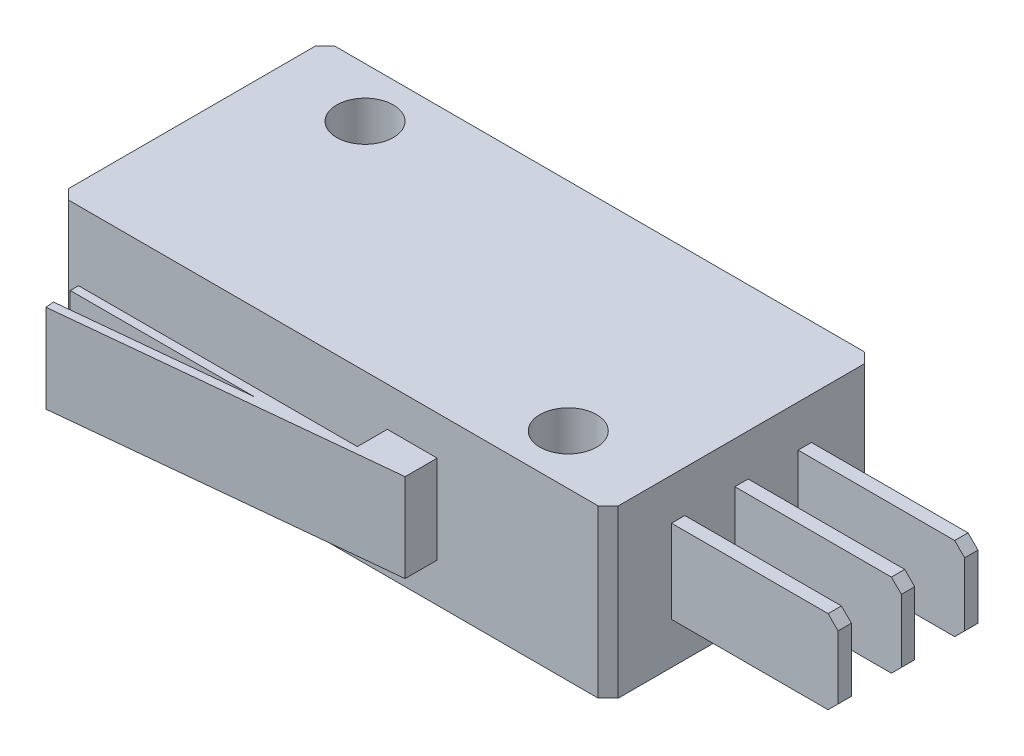
SolidWorks part; units mm, degrees
ref_plane "前视基准面" through (0, 0, 0) normal (0, 0, 1) x (1, 0, 0)
ref_plane "上视基准面" through (0, 0, 0) normal (0, 1, 0) x (1, 0, 0)
ref_plane "右视基准面" through (0, 0, 0) normal (1, 0, 0) x (0, 0, -1)
sketch "草图1" plane through (0, 0, 0) normal (0, 1, 0) x (1, 0, 0)
  line L0 (16.5, 0) -> (-16.5, 0) construction
  line L1 (-16.5, 8) -> (16.5, 8)
  line L2 (-16.5, 8) -> (-16.5, -8)
  line L3 (-16.5, -8) -> (16.5, -8)
  line L4 (16.5, 8) -> (16.5, -8)
  circle A0 centre (-11.1, 5) radius 1.7
  circle A1 centre (11.1, -5) radius 1.7
  point P4 (0, 8)
  point P6 (16.5, 0)
  dimension "D3" = 3.4
  dimension "D1" = 16
  dimension "D2" = 33
  dimension "D4" = 10
  dimension "D5" = 5
  dimension "D6" = 22.2
  dimension "D7" = 11.1
extrude "凸台-拉伸1" add sketch "草图1" along normal mid plane 10
sketch "草图2" plane through (0, 0, 0) normal (0, 1, 0) x (1, 0, 0)
  line L0 (3.237, -9.8) -> (-13.4989, -9.8)
  line L1 (-13.4989, -9.8) -> (-13.4989, -10.3)
  line L2 (-13.4989, -10.3) -> (-2.4578, -10.3)
  line L3 (6.2318, -9.9273) -> (6.2318, -4.6069)
  line L4 (3.237, -9.8) -> (3.237, -4.7223)
  line L5 (-13.3542, -11.9) -> (6.2318, -9.9273)
  line L7 (-13.4043, -11.4025) -> (-2.4578, -10.3)
  line L8 (-13.4043, -11.4025) -> (-13.3542, -11.9)
  arc A0 (6.2318, -4.6069) -> (3.237, -4.7223) centre (4.737, -4.7318) ccw
  circle A1 centre (-11.1, 5) radius 1.7 construction
  circle A2 centre (-11.1, 5) radius 1.7 construction
  dimension "D5" = 1.5
  dimension "D1" = 0.5
  dimension "D2" = 15.3
  dimension "D3" = 0.5
  dimension "D4" = 1.6
extrude "凸台-拉伸2" add sketch "草图2" along normal mid plane 5.3
sketch "草图3" plane through (16.5, 0, 0) normal (1, 0, 0) x (0, 0, -1)
  line L1 (-4.2, 2.5) -> (-3.4, 2.5)
  line L2 (-4.2, 2.5) -> (-4.2, -2.5)
  line L3 (-4.2, -2.5) -> (-3.4, -2.5)
  line L4 (-3.4, 2.5) -> (-3.4, -2.5)
  line L5 (-0.4, 2.5) -> (0.4, 2.5)
  line L6 (-0.4, 2.5) -> (-0.4, -2.5)
  line L7 (-0.4, -2.5) -> (0.4, -2.5)
  line L8 (0.4, 2.5) -> (0.4, -2.5)
  line L9 (3.4, 2.5) -> (4.2, 2.5)
  line L10 (3.4, 2.5) -> (3.4, -2.5)
  line L11 (3.4, -2.5) -> (4.2, -2.5)
  line L12 (4.2, 2.5) -> (4.2, -2.5)
  point P12 (-4.2, 0)
  point P14 (-0.4, 0)
  point P15 (3.4, 0)
  point P16 (0, 2.5)
  dimension "D1" = 3
  dimension "D2" = 3
  dimension "D3" = 0.8
  dimension "D4" = 5
extrude "凸台-拉伸3" add sketch "草图3" along normal blind 10
chamfer "倒角1" distance 0.6 angle 45 10 edges at (26.5, -2.5, 3.8) (26.5, 2.5, 3.8) (26.5, -2.5, 0) (26.5, 2.5, 0) (26.5, -2.5, -3.8) (26.5, 2.5, -3.8) (16.5, 0, -8) (16.5, 0, 8) (-16.5, 0, -8) (-16.5, 0, 8)
